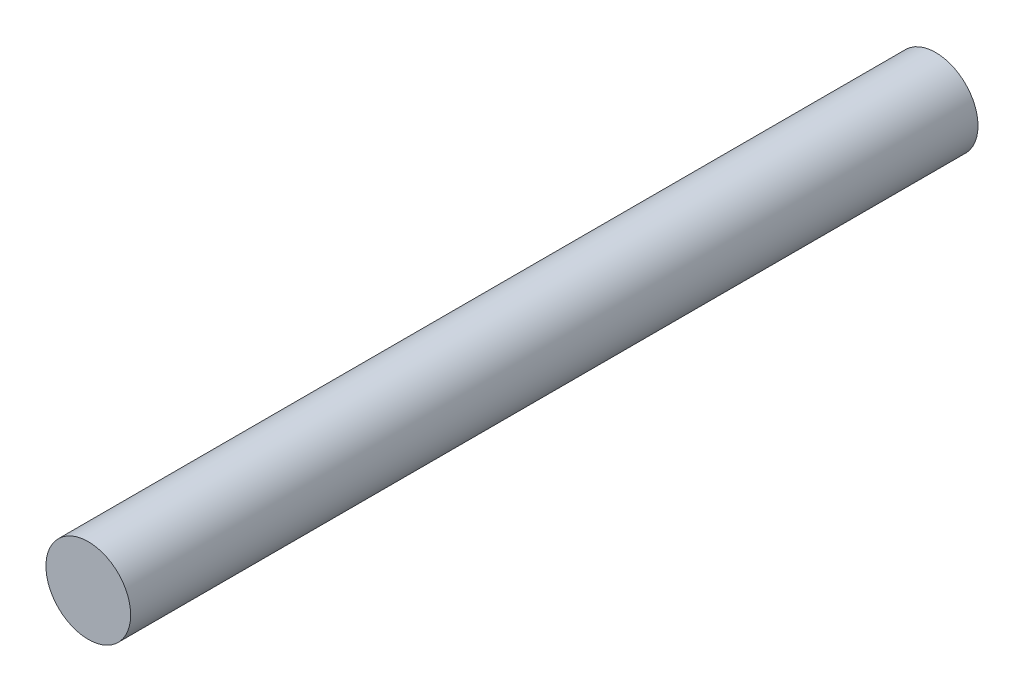
SolidWorks part; units mm, degrees
material "Хромистая нержавеющая сталь"
ref_plane "Спереди" through (0, 0, 0) normal (0, 0, 1) x (1, 0, 0)
ref_plane "Сверху" through (0, 0, 0) normal (0, 1, 0) x (1, 0, 0)
ref_plane "Справа" through (0, 0, 0) normal (1, 0, 0) x (0, 0, -1)
sketch "Эскиз1" plane through (0, 0, 0) normal (0, 0, 1) x (1, 0, 0)
  circle A0 centre (0, 0) radius 5
  dimension "D1" = 10
extrude "Бобышка-Вытянуть1" add sketch "Эскиз1" along normal blind 100
